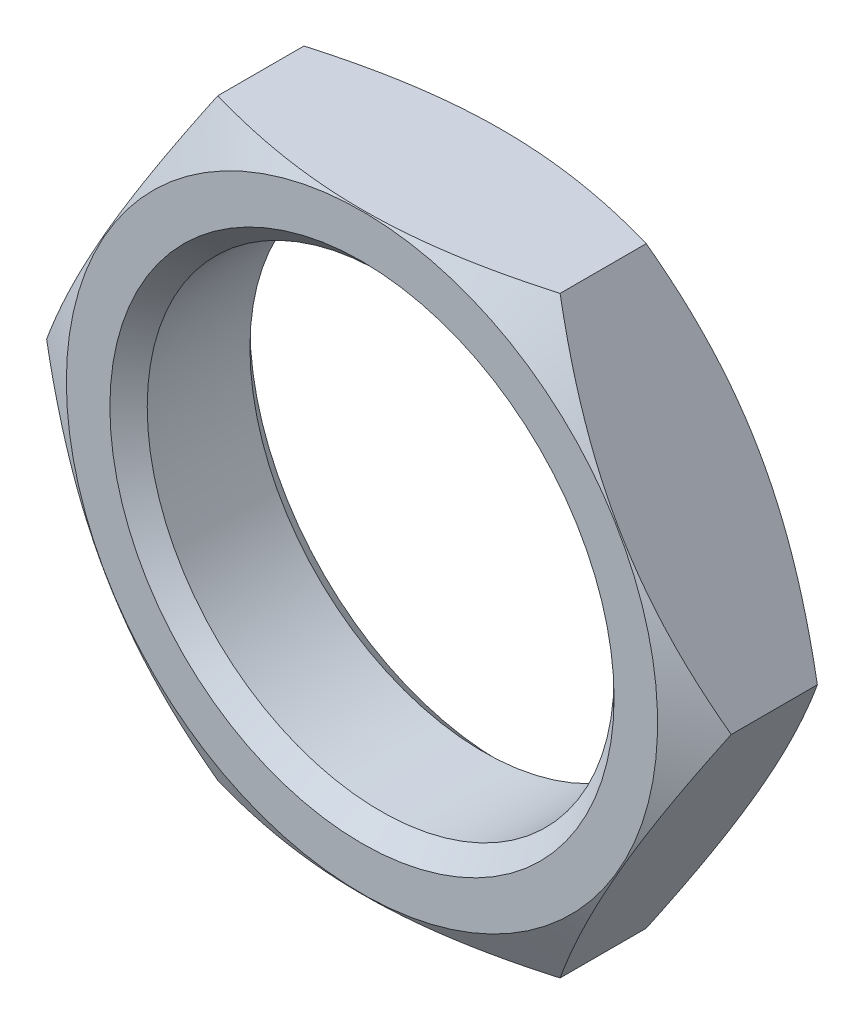
SolidWorks part; units mm, degrees
material "Laiton"
ref_plane "Plan de face" through (0, 0, 0) normal (0, 0, 1) x (1, 0, 0)
ref_plane "Plan de dessus" through (0, 0, 0) normal (0, 1, 0) x (1, 0, 0)
ref_plane "Plan de droite" through (0, 0, 0) normal (1, 0, 0) x (0, 0, -1)
sketch "Esquisse1" plane through (0, 0, 0) normal (0, 0, 1) x (1, 0, 0)
  line L1 (3.6662, 0) -> (1.8331, 3.175)
  line L2 (1.8331, 3.175) -> (-1.8331, 3.175)
  line L3 (-1.8331, 3.175) -> (-3.6662, 0)
  line L4 (-3.6662, 0) -> (-1.8331, -3.175)
  line L5 (-1.8331, -3.175) -> (1.8331, -3.175)
  line L6 (1.8331, -3.175) -> (3.6662, 0)
  circle A0 centre (0, 0) radius 3.175 construction
  circle A1 centre (0, 0) radius 2.5
  dimension "D2" = 5
  dimension "D1" = 6.35
extrude "Boss.-Extru.1" add sketch "Esquisse1" along normal blind 1.5
sketch "Esquisse2" plane through (0, 0, 0) normal (0, 1, 0) x (1, 0, 0)
  line L0 (-3.1662, 0) -> (-3.6662, -0.2887)
  line L1 (-3.6662, -0.2887) -> (-3.6662, -1.2113)
  line L2 (-3.6662, -1.2113) -> (-3.1662, -1.5)
  line L3 (-3.1662, -1.5) -> (-4.6662, -1.5)
  line L4 (-4.6662, -1.5) -> (-4.6662, 0)
  line L5 (-4.6662, 0) -> (-3.1662, 0)
  line L6 (-3.6662, -1.5) -> (-3.6662, 0) construction
  line L8 (-1.8331, 0) -> (-3.6662, 0) construction
  line L9 (-1.8331, -1.5) -> (-3.6662, -1.5) construction
  line L10 (-3.1662, 0) -> (-3.1662, -1.5) construction
  line L11 (0, 0) -> (0, -1.5) construction
  line L12 (1.8331, -1.5) -> (-1.8331, -1.5) construction
  dimension "D1" = 30
  dimension "D2" = 30
  dimension "D3" = 1
  dimension "D4" = 0.5
revolve "Enlèvement de matière-Révolution1" cut sketch "Esquisse2" angle 360 about L11
chamfer "Chanfrein1" distance 0.2 angle 45 2 edges at (2.5, 0, 1.5) (2.5, 0, 0)
